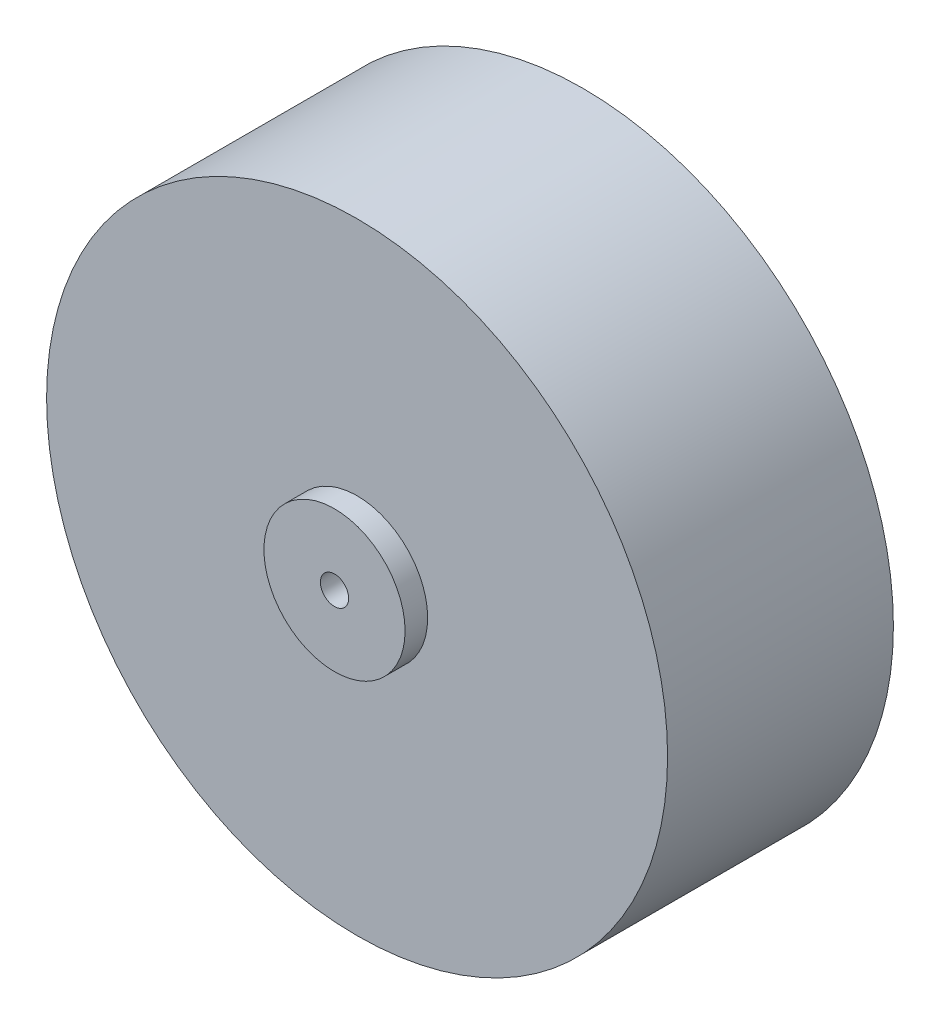
SolidWorks part; units mm, degrees
ref_plane "Front Plane" through (0, 0, 0) normal (0, 0, 1) x (1, 0, 0)
ref_plane "Top Plane" through (0, 0, 0) normal (0, 1, 0) x (1, 0, 0)
ref_plane "Right Plane" through (0, 0, 0) normal (1, 0, 0) x (0, 0, -1)
sketch "Sketch1" plane through (0, 0, 0) normal (0, 0, 1) x (1, 0, 0)
  circle A0 centre (0, 0) radius 55
  dimension "D1" = 110
extrude "Boss-Extrude1" add sketch "Sketch1" along normal mid plane 40
sketch "Sketch2" plane through (0, 0, 20) normal (0, 0, 1) x (1, 0, 0)
  circle A0 centre (0, 0) radius 12.5
  dimension "D1" = 25
extrude "Boss-Extrude2" add sketch "Sketch2" along normal blind 4
mirror "Mirror1" about plane through (0, 0, 0) normal (0, 0, 1) of "Boss-Extrude2"
sketch "KeySketch" plane through (6.6247, 1.2697, 24) normal (0, 0, 1) x (1, 0, 0)
  line L0 (-6.6247, -3.7697) -> (-6.6247, 2.2303) construction
  line L1 (-9.1247, -1.2697) -> (-4.1247, -1.2697) construction
  arc A0 (-7.6247, 1.0216) -> (-5.6247, 1.0216) centre (-6.6247, -1.2697) ccw
  circle A1 centre (-6.6247, -1.2697) radius 12.5 construction
  arc A2 (-7.6247, 1.0216) -> (-5.6247, 1.0216) centre (-6.6247, -1.2697) cw
  point P10 (-6.6247, 2.2303)
  dimension "Diameter" = 5
extrude "Keyway" cut sketch "KeySketch" against normal through all
other "bore with square keyway - parallel key<1>"
